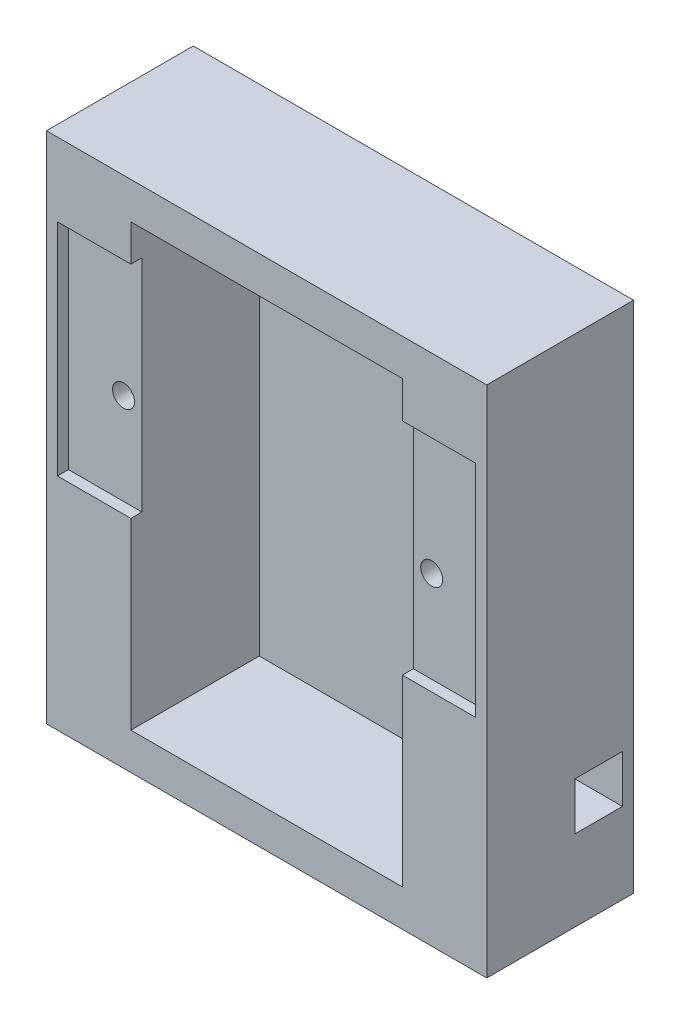
SolidWorks part; units mm, degrees
ref_plane "Front Plane" through (0, 0, 0) normal (0, 0, 1) x (1, 0, 0)
ref_plane "Top Plane" through (0, 0, 0) normal (0, 1, 0) x (1, 0, 0)
ref_plane "Right Plane" through (0, 0, 0) normal (1, 0, 0) x (0, 0, -1)
sketch "Sketch2" plane through (0, 0, 0) normal (0, 0, 1) x (1, 0, 0)
  line L1 (0, 0) -> (-120, 0)
  line L2 (0, 0) -> (0, -140)
  line L3 (0, -140) -> (-120, -140)
  line L4 (-120, 0) -> (-120, -140)
  dimension "D1" = 120
  dimension "D2" = 140
extrude "Boss-Extrude1" add sketch "Sketch2" along normal blind 40
sketch "Sketch3" plane through (0, 0, 40) normal (0, 0, 1) x (1, 0, 0)
  line L0 (0, 0) -> (-120, 0) construction
  line L1 (-97, -10) -> (-23, -10)
  line L2 (-97, -10) -> (-97, -130)
  line L3 (-97, -130) -> (-23, -130)
  line L4 (-23, -10) -> (-23, -130)
  line L6 (-120, -140) -> (0, -140) construction
  line L8 (-120, 0) -> (-120, -140) construction
  line L9 (0, -140) -> (0, 0) construction
  dimension "D1" = 10
  dimension "D2" = 23
  dimension "D3" = 10
  dimension "D4" = 23
extrude "Cut-Extrude1" cut sketch "Sketch3" against normal blind 35
sketch "Sketch4" plane through (0, 0, 40) normal (0, 0, 1) x (1, 0, 0)
  line L0 (-120, 0) -> (-120, -140) construction
  line L1 (0, -140) -> (0, 0) construction
  line L2 (0, 0) -> (-120, 0) construction
  circle A0 centre (-102, -55) radius 3
  circle A1 centre (-18, -55) radius 3
  dimension "D1" = 6
  dimension "D2" = 6
  dimension "D3" = 18
  dimension "D4" = 18
  dimension "D5" = 55
  dimension "D6" = 55
extrude "Cut-Extrude2" cut sketch "Sketch4" against normal blind 40
sketch "Sketch5" plane through (0, 0, 0) normal (1, 0, 0) x (0, 0, -1)
  line L0 (-40, -140) -> (0, -140) construction
  line L1 (-16, -105) -> (-3, -105)
  line L2 (-16, -105) -> (-16, -118)
  line L3 (-16, -118) -> (-3, -118)
  line L4 (-3, -105) -> (-3, -118)
  line L5 (0, -140) -> (0, 0) construction
  point P4 (-9.5, -118)
  dimension "D1" = 22
  dimension "D2" = 13
  dimension "D3" = 13
  dimension "D4" = 3
extrude "Cut-Extrude3" cut sketch "Sketch5" against normal blind 22
sketch "Sketch6" plane through (0, 0, 40) normal (0, 0, 1) x (1, 0, 0)
  line L0 (-97, -10) -> (-97, -130) construction
  line L1 (-117, -20) -> (-97, -20)
  line L2 (-117, -20) -> (-117, -80)
  line L3 (-117, -80) -> (-97, -80)
  line L4 (-97, -20) -> (-97, -80)
  line L5 (-23, -130) -> (-23, -10) construction
  line L6 (-23, -20) -> (-3, -20)
  line L7 (-23, -20) -> (-23, -80)
  line L8 (-23, -80) -> (-3, -80)
  line L9 (-3, -20) -> (-3, -80)
  line L10 (0, 0) -> (-120, 0) construction
  line L11 (0, -140) -> (0, 0) construction
  line L12 (-120, 0) -> (-120, -140) construction
  point P12 (-107, -20)
  dimension "D1" = 60
  dimension "D2" = 60
  dimension "D3" = 20
  dimension "D4" = 20
  dimension "D5" = 3
  dimension "D6" = 3
extrude "Cut-Extrude4" cut sketch "Sketch6" against normal blind 3
